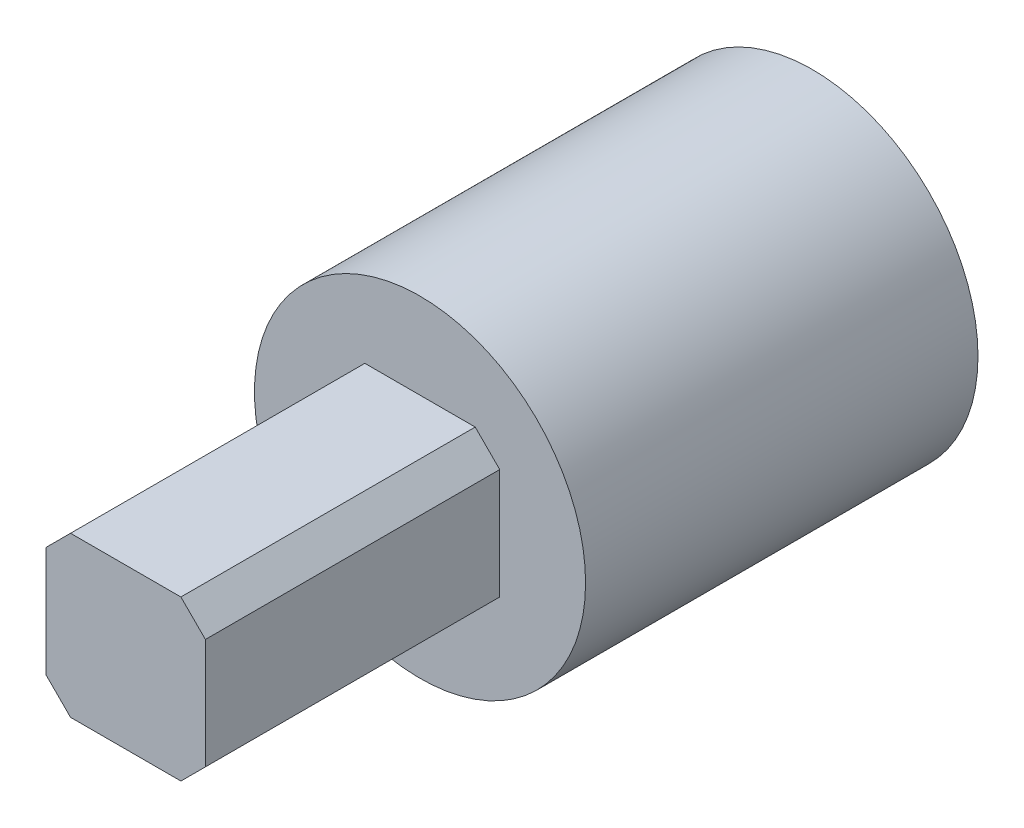
SolidWorks part; units mm, degrees
ref_plane "Front Plane" through (0, 0, 0) normal (0, 0, 1) x (1, 0, 0)
ref_plane "Top Plane" through (0, 0, 0) normal (0, 1, 0) x (1, 0, 0)
ref_plane "Right Plane" through (0, 0, 0) normal (1, 0, 0) x (0, 0, -1)
sketch "Sketch1" plane through (0, 0, 0) normal (0, 0, 1) x (1, 0, 0)
  circle A0 centre (0, 0) radius 13.5
  dimension "D1" = 27
extrude "Boss-Extrude1" add sketch "Sketch1" along normal blind 32 contours A0
sketch "Sketch2" plane through (0, 0, 32) normal (0, 0, 1) x (1, 0, 0)
  line L0 (-6.5, 4.5) -> (-4.5, 6.5)
  line L5 (-4.5, -6.5) -> (4.5, -6.5)
  line L6 (-6.5, -4.5) -> (-6.5, 4.5)
  line L7 (-4.5, 6.5) -> (4.5, 6.5)
  line L8 (6.5, -4.5) -> (6.5, 4.5)
  line L9 (-6.5, -6.5) -> (6.5, 6.5) construction
  line L10 (-6.5, 6.5) -> (6.5, -6.5) construction
  line L11 (4.5, 6.5) -> (6.5, 4.5)
  line L12 (4.5, -6.5) -> (6.5, -4.5)
  line L13 (-6.5, -4.5) -> (-4.5, -6.5)
  point P0 (0, 0)
  dimension "D1" = 13
  dimension "D2" = 13
extrude "Boss-Extrude2" add sketch "Sketch2" along normal blind 24
